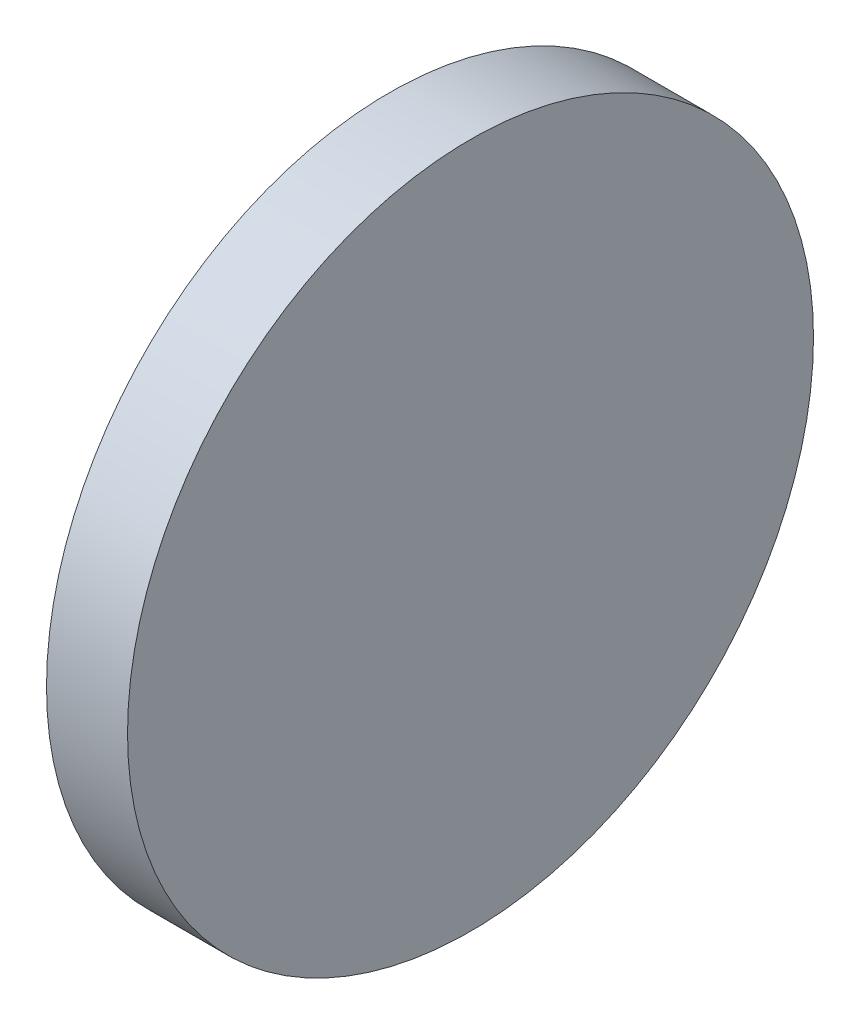
SolidWorks part; units mm, degrees
ref_plane "Front Plane" through (0, 0, 0) normal (0, 0, 1) x (1, 0, 0)
ref_plane "Top Plane" through (0, 0, 0) normal (0, 1, 0) x (1, 0, 0)
ref_plane "Right Plane" through (0, 0, 0) normal (1, 0, 0) x (0, 0, -1)
sketch "Axial profile (mm)" plane through (0, 0, 0) normal (0, 0, 1) x (1, 0, 0)
  line L0 (-110, 0) -> (75, 0) construction
  line L1 (168.7, 0) -> (174.7, 0)
  line L2 (174.7, 0) -> (174.7, 25.4)
  line L3 (174.7, 25.4) -> (168.7, 25.4)
  line L4 (168.7, 25.4) -> (168.7, 0)
revolve "Full revolution" add sketch "Axial profile (mm)" angle 360 about L0
